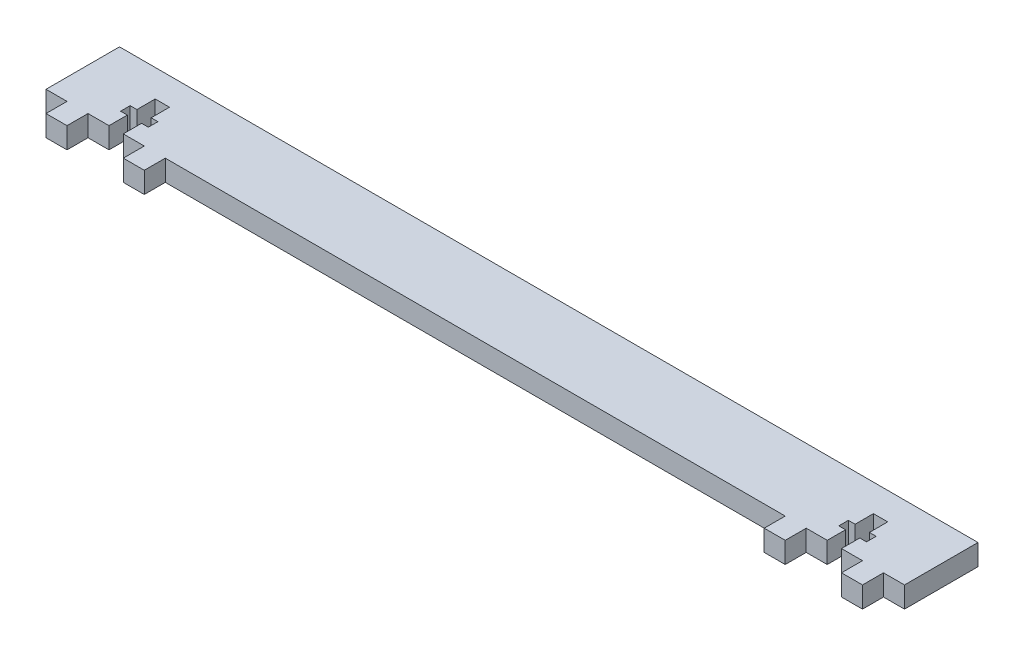
SolidWorks part; units mm, degrees
ref_plane "Front Plane" through (0, 0, 0) normal (0, 0, 1) x (1, 0, 0)
ref_plane "Top Plane" through (0, 0, 0) normal (0, 1, 0) x (1, 0, 0)
ref_plane "Right Plane" through (0, 0, 0) normal (1, 0, 0) x (0, 0, -1)
sketch "Sketch1" plane through (0, 0, 0) normal (0, 1, 0) x (1, 0, 0)
  line L0 (0, 11.1125) -> (0, -11.1125) construction
  line L1 (-129.794, -11.1125) -> (-123.444, -11.1125)
  line L2 (-129.794, -11.1125) -> (-129.794, 11.1125)
  line L3 (-129.794, 11.1125) -> (129.794, 11.1125)
  line L4 (129.794, -11.1125) -> (129.794, 11.1125)
  line L5 (-129.794, -11.1125) -> (129.794, 11.1125) construction
  line L6 (-129.794, 11.1125) -> (129.794, -11.1125) construction
  line L7 (-93.726, -11.1125) -> (93.726, -11.1125)
  line L8 (129.794, -11.1125) -> (123.444, -11.1125)
  point P0 (0, 0)
  line B0 (-117.094, -11.1125) -> (-117.094, -17.4625)
  line B1 (-117.094, -17.4625) -> (-123.444, -17.4625)
  line B2 (-123.444, -17.4625) -> (-123.444, -11.1125)
  line B3 (-110.744, -11.1125) -> (-110.744, -5.5775)
  line B4 (-110.744, -5.5775) -> (-112.785, -5.5775)
  line B5 (-112.785, -5.5775) -> (-112.785, -2.6775)
  line B6 (-112.785, -2.6775) -> (-110.744, -2.6775)
  line B7 (-110.744, -2.6775) -> (-110.744, 2.8575)
  line B8 (-110.744, 2.8575) -> (-106.426, 2.8575)
  line B9 (-106.426, 2.8575) -> (-106.426, -2.6775)
  line B10 (-106.426, -2.6775) -> (-104.385, -2.6775)
  line B11 (-104.385, -2.6775) -> (-104.385, -5.5775)
  line B12 (-104.385, -5.5775) -> (-106.426, -5.5775)
  line B13 (-106.426, -5.5775) -> (-106.426, -11.1125)
  line B14 (-108.585, 2.8575) -> (-108.585, -11.1125) construction
  line B15 (-100.076, -11.1125) -> (-106.426, -11.1125)
  line B16 (-93.726, -17.4625) -> (-93.726, -11.1125)
  line B17 (-117.094, -11.1125) -> (-110.744, -11.1125)
  line B18 (-100.076, -17.4625) -> (-93.726, -17.4625)
  line B19 (-100.076, -11.1125) -> (-100.076, -17.4625)
  line B20 (117.094, -11.1125) -> (117.094, -17.4625)
  line B21 (117.094, -17.4625) -> (123.444, -17.4625)
  line B22 (123.444, -17.4625) -> (123.444, -11.1125)
  line B23 (110.744, -11.1125) -> (110.744, -5.5775)
  line B24 (110.744, -5.5775) -> (112.785, -5.5775)
  line B25 (112.785, -5.5775) -> (112.785, -2.6775)
  line B26 (112.785, -2.6775) -> (110.744, -2.6775)
  line B27 (110.744, -2.6775) -> (110.744, 2.8575)
  line B28 (110.744, 2.8575) -> (106.426, 2.8575)
  line B29 (106.426, 2.8575) -> (106.426, -2.6775)
  line B30 (106.426, -2.6775) -> (104.385, -2.6775)
  line B31 (104.385, -2.6775) -> (104.385, -5.5775)
  line B32 (104.385, -5.5775) -> (106.426, -5.5775)
  line B33 (106.426, -5.5775) -> (106.426, -11.1125)
  line B34 (108.585, 2.8575) -> (108.585, -11.1125) construction
  line B35 (100.076, -11.1125) -> (106.426, -11.1125)
  line B36 (93.726, -17.4625) -> (93.726, -11.1125)
  line B37 (117.094, -11.1125) -> (110.744, -11.1125)
  line B38 (100.076, -17.4625) -> (93.726, -17.4625)
  line B39 (100.076, -11.1125) -> (100.076, -17.4625)
  dimension "D1" = 22.225
  dimension "D2" = 187.452
  dimension "D3" = 6.35
sketch_block_instance "Male T-slot assembly-1"
sketch_block "Male T-slot assembly" parameters "D1"=6.35, "D2"=6.35, "D3"=4.318, "D4"=2.9, "D5"=8.4, "D6"=13.97, "D7"=6.35
sketch_block_instance "Male T-slot assembly-3"
extrude "Boss-Extrude1" add sketch "Sketch1" along normal blind 6.35 contours B39 B35 B33 B32 B31 B30 B29 B28 B27 B26 B25 B24 B23 B37 B20 B21 B22 L8 L4 L3 L2 L1 B2 B1 B0 B17 B3 B4 B5 B6 B7 B8 B9 B10 B11 B12 B13 B15 B19 B18 B16 L7 B36 B38
equation "\"Ball Diameter\"= 1.75in"
equation "\"Ball Radius\" = \"Ball Diameter\"/2"
equation "\"Sheet Thickness\"= 0.25in"
equation "\"Screw Diameter\"= .17in"
equation "\"Robot Diameter\"= 14in"
equation "\"Castor Screw Diameter\"= 0.22in"
equation "\"Wheel Diameter\" = 4in"
equation "\"Nut Diameter\" = 8.4mm"
equation "\"Nut Height\" = 2.9mm"
equation "\"Screw Height\" = 0.55in"
equation "\"Pulley Diameter\" = 1in"
equation "\"Reactor Height\" = 14in"
equation "\"Elevator Height\" = 11.5in"
equation "\"Elevator Width\" = \"Ball Diameter\" + 0.25in"
equation "\"Elevator Bearing Diameter\" = sqr(2*(\"Sheet Thickness\"^2)) + 0.2in"
equation "\"Elevator Axle Endcap Diameter\" = \"Pulley Diameter\" + 0.25in"
equation "\"Elevator Axle Length\" = \"Elevator Width\" + 8*\"Sheet Thickness\""
equation "\"Elevator Clearance from Axis\" = 3.28in"
equation "\"Elevator Horizontal Clearance\" = \"Elevator Width\" + 0.5in"
equation "\"Claw Horizontal Seperation\" = (\"Elevator Width\"/2) - (1.5 * \"Sheet Thickness\") - 0.15in"
equation "\"Claw Radius\" = \"Ball Radius\" + 0.1in"
equation "\"Castor Wheel Height\" = 1.25in"
equation "\"Length of Chute\" = 8in"
equation "\"D1@Sketch1\"=\"Ball Radius\""
